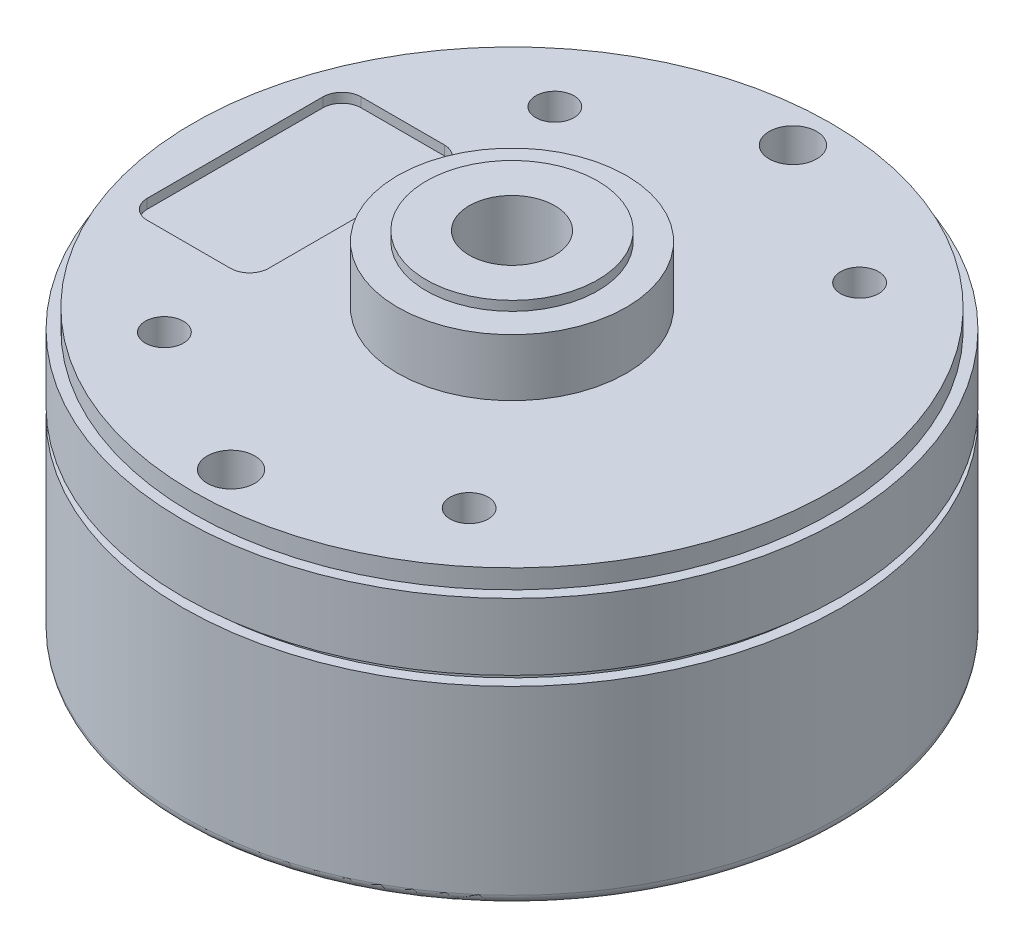
SolidWorks part; units mm, degrees
material "6061 合金"
ref_plane "前视基准面" through (0, 0, 0) normal (0, 0, 1) x (1, 0, 0)
ref_plane "上视基准面" through (0, 0, 0) normal (0, 1, 0) x (1, 0, 0)
ref_plane "右视基准面" through (0, 0, 0) normal (1, 0, 0) x (0, 0, -1)
sketch "草图1" plane through (0, 0, 0) normal (0, 0, 1) x (1, 0, 0)
  line L0 (0, 0) -> (0, 8.625) construction
  line L1 (2.25, 0) -> (2.25, 18.5)
  line L2 (2.25, 18.5) -> (4.5, 18.5)
  line L3 (4.5, 18.5) -> (4.5, 18)
  line L4 (4.5, 18) -> (6, 18)
  line L5 (6, 18) -> (6, 15)
  line L6 (6, 15) -> (16.75, 15)
  line L7 (16.75, 15) -> (16.75, 14)
  line L8 (16.75, 14) -> (17.3, 14)
  line L9 (17.3, 14) -> (17.3, 10.5)
  line L10 (17.3, 10.5) -> (16.75, 10.5)
  line L11 (16.75, 10.5) -> (16.75, 10)
  line L12 (16.75, 10) -> (17.3, 10)
  line L13 (17.3, 10) -> (17.3, 0)
  line L14 (17.3, 0) -> (2.25, 0)
  dimension "D1" = 4.5
  dimension "D2" = 34.6
  dimension "D3" = 33.5
  dimension "D4" = 15
  dimension "D5" = 1
  dimension "D6" = 12
  dimension "D7" = 3
  dimension "D8" = 0.5
  dimension "D9" = 0.5
  dimension "D10" = 1.5
  dimension "D11" = 3.5
revolve "旋转1" add sketch "草图1" angle 360 about L0
fillet "圆角1" radius 0.5 1 edges at (0, 0, -17.3)
sketch "草图2" plane through (0, 15, 0) normal (0, 1, 0) x (1, 0, 0)
  line L0 (-10.175, 0) -> (10.175, 0) construction
  line L1 (-8, -10.25) -> (8, -10.25) construction
  line L2 (-8, -10.25) -> (-8, 10.25) construction
  line L3 (-8, 10.25) -> (8, 10.25) construction
  line L4 (8, -10.25) -> (8, 10.25) construction
  line L5 (-8, -10.25) -> (8, 10.25) construction
  line L6 (-8, 10.25) -> (8, -10.25) construction
  circle A0 centre (-8, 10.25) radius 1
  circle A1 centre (8, 10.25) radius 1
  circle A2 centre (8, -10.25) radius 1
  circle A3 centre (-8, -10.25) radius 1
  circle A4 centre (0, 14.75) radius 1.25
  circle A5 centre (0, -14.75) radius 1.25
  point P0 (0, 0)
  dimension "D3" = 2
  dimension "D4" = 2.5
  dimension "D5" = 29.5
  dimension "D1" = 20.5
  dimension "D2" = 16
extrude "切除-拉伸1" cut sketch "草图2" against normal blind 4
sketch "草图3" plane through (0, 0, 0) normal (0, -1, 0) x (1, 0, 0)
  circle A1 centre (0, 6.25) radius 1
  circle A2 centre (5.25, 5.25) radius 1.25
  circle A3 centre (6.25, 0) radius 1
  circle A4 centre (5.25, -5.25) radius 1.25
  circle A5 centre (0, -6.25) radius 1
  circle A6 centre (-5.25, -5.25) radius 1.25
  circle A7 centre (-6.25, 0) radius 1
  circle A8 centre (-5.25, 5.25) radius 1.25
  point P20 (0, 0)
  dimension "D1" = 2
  dimension "D2" = 2.5
  dimension "D4" = 10.5
  dimension "D5" = 12.5
  dimension "D3" = 4
extrude "切除-拉伸2" cut sketch "草图3" against normal blind 4
sketch "草图4" plane through (0, 0, 0) normal (0, -1, 0) x (1, 0, 0)
  circle A0 centre (0, 0) radius 3.2
  dimension "D1" = 6.4
extrude "切除-拉伸3" cut sketch "草图4" against normal blind 1
sketch "草图5" plane through (0, 15, 0) normal (0, 1, 0) x (1, 0, 0)
  line L1 (-13.5382, -5.614) -> (-9.1651, -5.614)
  line L2 (-14.5382, -4.614) -> (-14.5382, 4.614)
  line L3 (-13.5382, 5.614) -> (-9.1651, 5.614)
  line L4 (-8.1651, -4.614) -> (-8.1651, 4.614)
  line L5 (-14.5382, -5.614) -> (-8.1651, 5.614) construction
  line L6 (-14.5382, 5.614) -> (-8.1651, -5.614) construction
  arc A0 (-9.1651, -5.614) -> (-8.1651, -4.614) centre (-9.1651, -4.614) ccw
  arc A1 (-13.5382, -5.614) -> (-14.5382, -4.614) centre (-13.5382, -4.614) cw
  arc A2 (-9.1651, 5.614) -> (-8.1651, 4.614) centre (-9.1651, 4.614) cw
  arc A3 (-14.5382, 4.614) -> (-13.5382, 5.614) centre (-13.5382, 4.614) cw
  circle A4 centre (0, 0) radius 14.75 construction
  point P0 (-11.3516, 0)
  dimension "D1" = 1
extrude "切除-拉伸4" cut sketch "草图5" against normal blind 0.5
